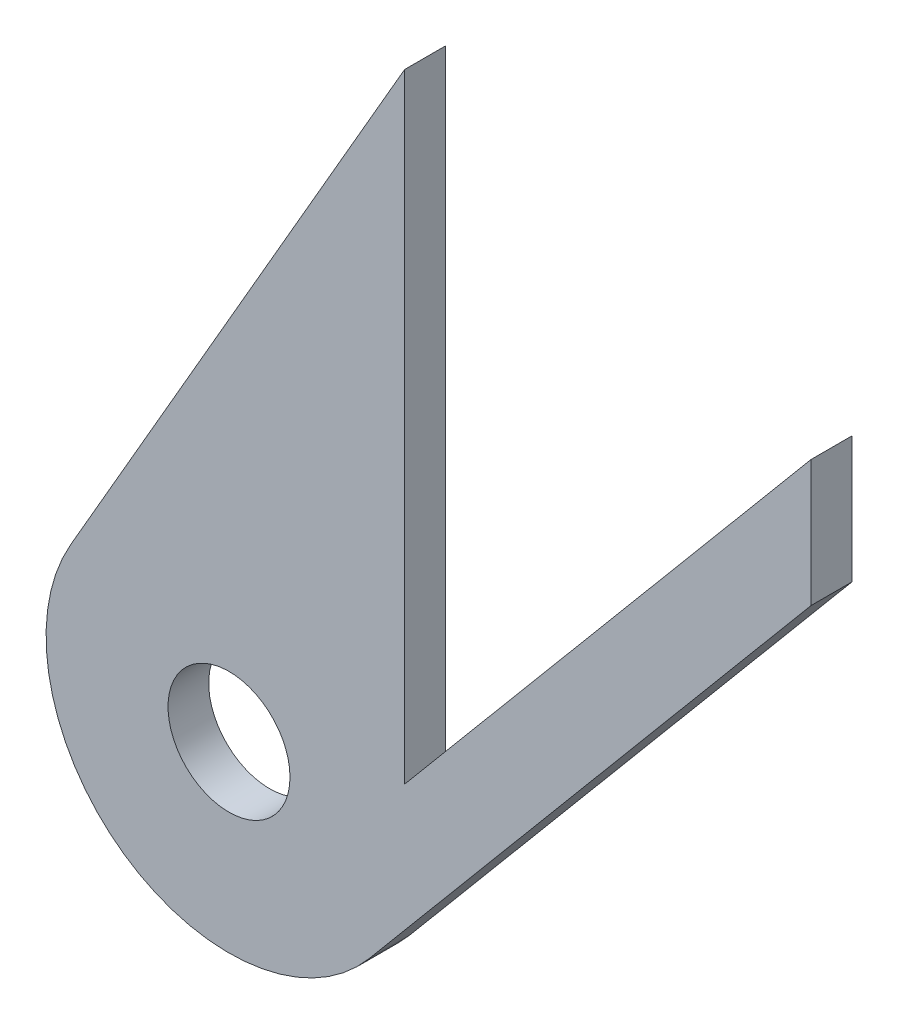
SolidWorks part; units mm, degrees
ref_plane "Plan de face" through (0, 0, 0) normal (0, 0, 1) x (1, 0, 0)
ref_plane "Plan de dessus" through (0, 0, 0) normal (0, 1, 0) x (1, 0, 0)
ref_plane "Plan de droite" through (0, 0, 0) normal (1, 0, 0) x (0, 0, -1)
sketch "Esquisse1" plane through (0, 0, 0) normal (0, 0, 1) x (1, 0, 0)
  line L0 (0, 0) -> (143.202, 0) construction
  line L1 (0, 0) -> (43.202, 74.8281) construction
  line L2 (143.202, 100.654) -> (143.202, 0) construction
  line L3 (43.202, 1057.7684) -> (43.202, 12.5931) construction
  line L4 (43.202, 12.5931) -> (143.202, 131.7684) construction
  line L5 (143.202, 131.7684) -> (143.202, 1057.7684) construction
  line L6 (143.202, 1057.7684) -> (43.202, 1057.7684) construction
  line L7 (43.202, 12.5931) -> (43.202, 74.8281) construction
  line L8 (-38.9711, 22.5) -> (43.202, 164.8281)
  line L9 (34.472, -28.9254) -> (143.202, 100.654)
  line L10 (143.202, 100.654) -> (143.202, 131.7684)
  line L11 (143.202, 131.7684) -> (43.202, 12.5931)
  line L12 (43.202, 12.5931) -> (43.202, 164.8281)
  circle A0 centre (0, 0) radius 15
  circle A1 centre (0, 0) radius 45 construction
  arc A2 (-38.9711, 22.5) -> (34.472, -28.9254) centre (0, 0) ccw
  dimension "D1" = 30
  dimension "D5" = 30
  dimension "D2" = 30
  dimension "D3" = 100
  dimension "D4" = 40
  dimension "D6" = 926
  dimension "D7" = 30
  dimension "D8" = 20
extrude "Boss.-Extru.1" add sketch "Esquisse1" along normal blind 10
